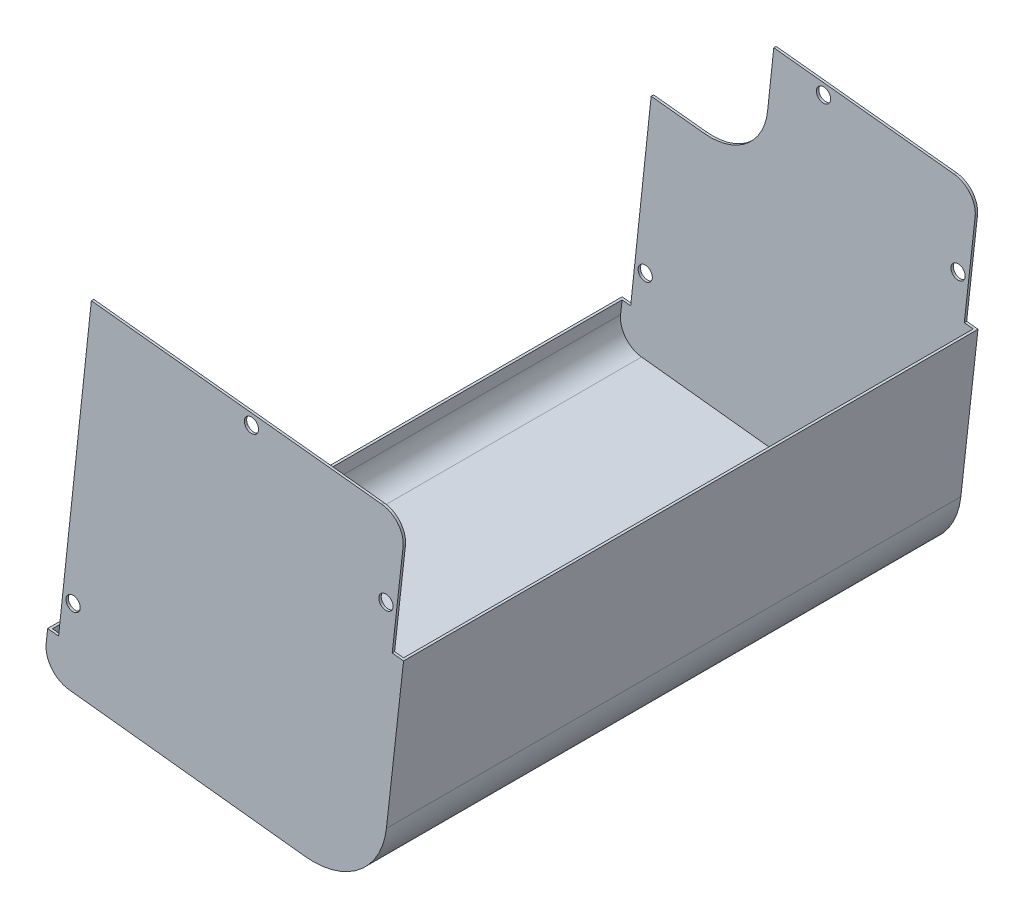
SolidWorks part; units mm, degrees
ref_plane "前视基准面" through (0, 0, 0) normal (0, 0, 1) x (1, 0, 0)
ref_plane "上视基准面" through (0, 0, 0) normal (0, 1, 0) x (1, 0, 0)
ref_plane "右视基准面" through (0, 0, 0) normal (1, 0, 0) x (0, 0, -1)
sketch "草图1" plane through (0, 0, 0) normal (0, 0, 1) x (1, 0, 0)
  line L0 (-59.3159, -68.0278) -> (-59.9536, -73.7467)
  line L1 (-51.1233, -84.7933) -> (48.2608, -95.8747)
  line L2 (89.4085, 36.7284) -> (84.8371, -4.2707)
  line L3 (88.6137, -4.6918) -> (81.4004, -69.3839)
  line L5 (88.6137, -4.6918) -> (84.8371, -4.2707)
  line L9 (-59.1904, -68.0412) -> (-59.3159, -68.0278)
  line L11 (80.5317, 47.78) -> (-41.9089, 60.8525)
  line L15 (-41.9089, 60.8525) -> (-55.7101, -68.4128)
  line L18 (-59.1904, -68.0412) -> (-55.7101, -68.4128)
  arc A0 (81.4004, -69.3839) -> (48.2608, -95.8747) centre (51.5852, -66.0594) cw
  arc A1 (-51.1233, -84.7933) -> (-59.9536, -73.7467) centre (-50.0152, -74.8549) cw
  arc A2 (89.4085, 36.7284) -> (80.5317, 47.78) centre (79.4701, 37.8365) ccw
  point P0 (0, 0)
  point P8 (-61.0617, -83.6851)
  point P16 (-58.9399, -82.6504)
  dimension "D1" = 10
  dimension "D3" = 10
  dimension "D2" = 30
extrude "凸台-拉伸1" add sketch "草图1" along normal blind 240
shell "抽壳1" thickness 1
sketch "草图2" plane through (0, 0, -1) normal (0, 0, -1) x (-1, 0, 0)
  line L1 (41.9089, 60.8525) -> (55.7101, -68.4128) construction
  line L4 (47.0842, 12.3803) -> (24.7113, 9.9916)
  line L5 (41.9089, 60.8525) -> (47.0842, 12.3803)
  line L7 (-80.5317, 47.78) -> (41.9089, 60.8525) construction
  line L8 (-4.5747, 55.8896) -> (41.9089, 60.8525)
  line L9 (-6.5634, 55.6773) -> (41.9089, 60.8525) construction
  line L10 (41.9089, 60.8525) -> (47.2965, 10.3916) construction
  line L12 (-1.9737, 31.5281) -> (-4.5747, 55.8896)
  line L13 (45.0955, 12.1679) -> (24.7113, 9.9916) construction
  line L14 (-1.9737, 31.5281) -> (-4.3623, 53.901) construction
  line L15 (47.2965, 10.3916) -> (24.9236, 8.0029) construction
  line L16 (-3.9624, 31.3158) -> (-6.5634, 55.6773) construction
  line L17 (-4.3623, 53.901) -> (40.1326, 58.6515) construction
  line L18 (40.1326, 58.6515) -> (45.0955, 12.1679) construction
  arc A1 (-1.9737, 31.5281) -> (24.7113, 9.9916) centre (22.1371, 34.1023) ccw
  arc A3 (-3.9624, 31.3158) -> (24.9236, 8.0029) centre (22.1371, 34.1023) ccw construction
extrude "切除-拉伸1" cut sketch "草图2" against normal blind 10
sketch "草图3" plane through (0, 0, -1) normal (0, 0, -1) x (-1, 0, 0)
  circle A0 centre (-25.5273, 49.127) radius 3
  circle A1 centre (-82.2022, 12.9055) radius 3
  circle A2 centre (49.59, -53.4781) radius 3
  dimension "D1" = 6
extrude "切除-拉伸2" cut sketch "草图3" against normal blind 10
sketch "草图6" plane through (0, 0, 241) normal (0, 0, 1) x (1, 0, 0)
  circle A0 centre (25.5273, 49.127) radius 3
  circle A1 centre (82.2022, 12.9055) radius 3
  circle A2 centre (-49.59, -53.4781) radius 3
  dimension "D1" = 6
extrude "切除-拉伸4" cut sketch "草图6" against normal blind 8
